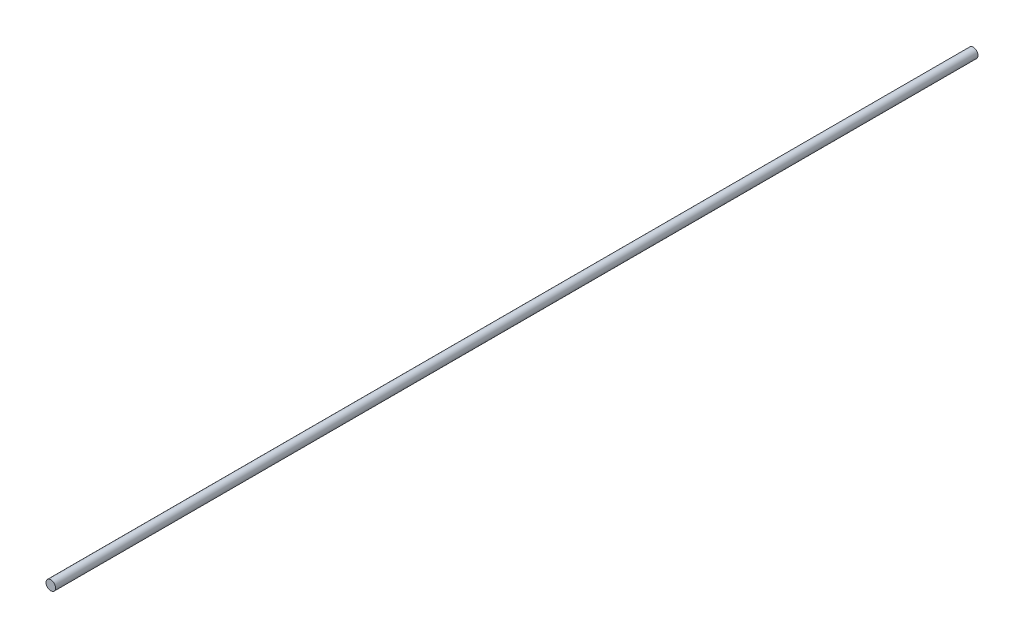
SolidWorks part; units mm, degrees
ref_plane "Ebene vorne" through (0, 0, 0) normal (0, 0, 1) x (1, 0, 0)
ref_plane "Ebene oben" through (0, 0, 0) normal (0, 1, 0) x (1, 0, 0)
ref_plane "Ebene rechts" through (0, 0, 0) normal (1, 0, 0) x (0, 0, -1)
sketch "Skizze1" plane through (0, 0, 0) normal (0, 0, 1) x (1, 0, 0)
  circle A0 centre (0, 0) radius 4
  dimension "D1" = 8
extrude "Aufsatz-Linear austragen1" add sketch "Skizze1" along normal blind 770
